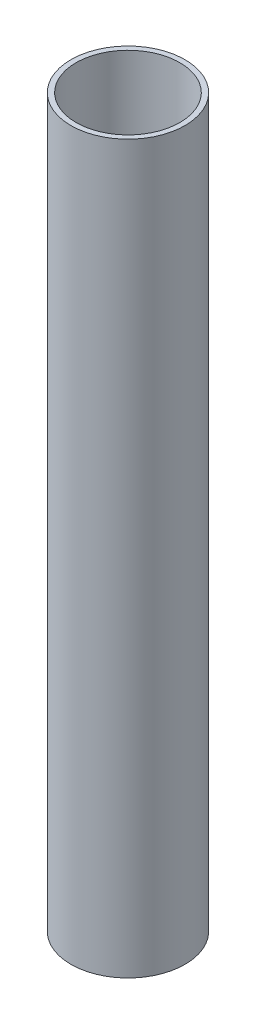
SolidWorks part; units mm, degrees
ref_plane "Front Plane" through (0, 0, 0) normal (0, 0, 1) x (1, 0, 0)
ref_plane "Top Plane" through (0, 0, 0) normal (0, 1, 0) x (1, 0, 0)
ref_plane "Right Plane" through (0, 0, 0) normal (1, 0, 0) x (0, 0, -1)
sketch "Sketch1" plane through (0, 0, 0) normal (0, 1, 0) x (1, 0, 0)
  circle A0 centre (0, 0) radius 55
  circle A1 centre (0, 0) radius 50
  dimension "D1" = 110
  dimension "D2" = 100
extrude "Boss-Extrude1" add sketch "Sketch1" along normal blind 700
